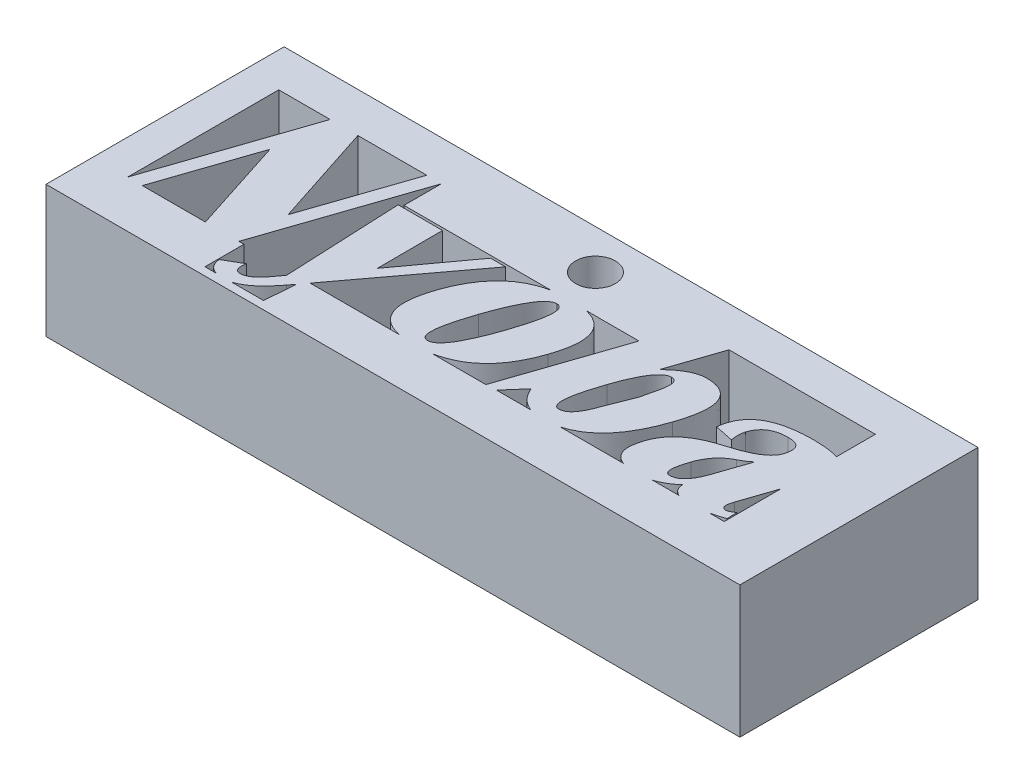
SolidWorks part; units mm, degrees
ref_plane "Front Plane" through (0, 0, 0) normal (0, 0, 1) x (1, 0, 0)
ref_plane "Top Plane" through (0, 0, 0) normal (0, 1, 0) x (1, 0, 0)
ref_plane "Right Plane" through (0, 0, 0) normal (1, 0, 0) x (0, 0, -1)
sketch "Sketch1" plane through (0, 0, 0) normal (0, 1, 0) x (1, 0, 0)
  text T0 "Nyoba" font "Britannic Bold" height in points 48
extrude "Boss-Extrude1" add sketch "Sketch1" along normal blind 10
sketch "Sketch2" plane through (0, 10, 0) normal (0, 1, 0) x (1, 0, 0)
  line L10 (9.7725, 0) -> (9.7725, -2.9509)
  line L17 (9.7725, -2.9509) -> (14.2071, -2.9509)
  line L22 (0.955, 0) -> (9.7725, 0)
  line L23 (-1.6675, -3.5637) -> (50.9358, -3.5637)
  line L24 (-1.6675, -3.5637) -> (-1.6675, 14.4875)
  line L25 (-1.6675, 14.4875) -> (50.9358, 14.4875)
  line L26 (50.9358, -3.5637) -> (50.9358, 14.4875)
  line L27 (14.2071, -2.9509) -> (14.4006, -0.6187)
  line L28 (9.7725, -3.5637) -> (14.4006, -3.5637)
  line L29 (31.1018, 8.6211) -> (13.2852, 8.6211)
  line L30 (21.1712, 8.4357) -> (14.0636, -1.0694) construction
  line L31 (14.4006, -0.6187) -> (14.8322, -0.0415)
  line L32 (14.8322, -0.0415) -> (28.1578, -0.0415)
  line L33 (28.1719, 0) -> (32.0665, 11.4598) construction
  line L34 (28.1578, -0.0415) -> (28.1719, 0)
  line L35 (28.1719, 0) -> (46.1827, 0)
  line L36 (46.1827, 0) -> (46.1827, 11.4598)
  line L37 (46.1827, 11.4598) -> (32.0665, 11.4598)
  line L38 (32.0665, 11.4598) -> (31.1018, 8.6211)
  line L39 (13.2852, 8.6211) -> (13.2852, 11.4598)
  line L40 (13.2852, 11.4598) -> (0.955, 11.4598)
  line L41 (0.955, 11.4598) -> (0.955, 0)
  line M1 (13.2852, 11.4598) -> (12.171, 11.4598)
  line M4 (6.9535, 11.4598) -> (4.8495, 11.4598)
  line M6 (0.955, 0) -> (2.0691, 0)
  line M9 (6.8515, 0) -> (9.3906, 0)
extrude "Boss-Extrude5" add sketch "Sketch2" against normal up to surface (10 mm away) contours L23 L26 L25 L24 L41 L40 L39 L29 L38 L37 L36 L35 L34 L32 L31 L27 L17 L10 L22 M4 M1 M9 M6 up to face at (24.3023, 0, -4.2974)
sketch "Sketch3" plane through (0, 10, 0) normal (0, 1, 0) x (1, 0, 0)
  line L0 (-1.6675, 14.4875) -> (50.9358, 14.4875) construction
  line L1 (50.9358, -3.5637) -> (50.9358, 14.4875) construction
  circle A0 centre (24.9358, 11.4875) radius 1.5
  dimension "D1" = 3
  dimension "D3" = 3
  dimension "D2" = 26
extrude "Cut-Extrude1" cut sketch "Sketch3" against normal blind 10
